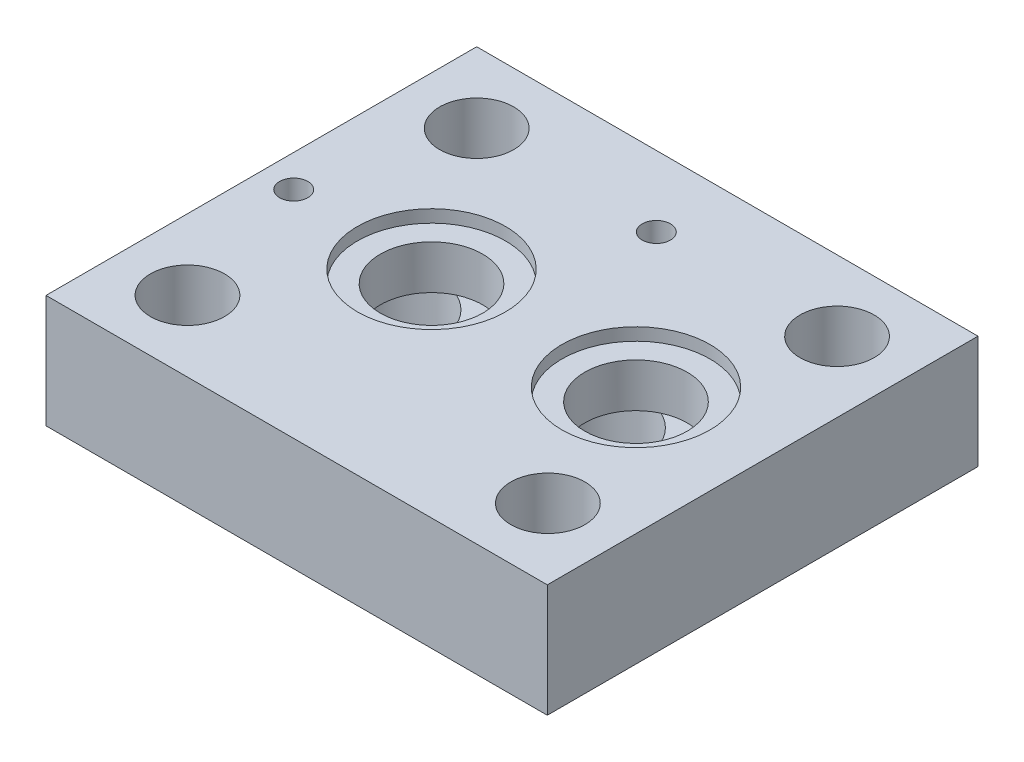
SolidWorks part; units mm, degrees
ref_plane "Front Plane" through (0, 0, 0) normal (0, 0, 1) x (1, 0, 0)
ref_plane "Top Plane" through (0, 0, 0) normal (0, 1, 0) x (1, 0, 0)
ref_plane "Right Plane" through (0, 0, 0) normal (1, 0, 0) x (0, 0, -1)
sketch "Sketch1" plane through (0, 0, 0) normal (0, 1, 0) x (1, 0, 0)
  line L1 (-56.3562, -48.4187) -> (56.3562, -48.4187)
  line L2 (-56.3562, -48.4187) -> (-56.3562, 48.4187)
  line L3 (-56.3562, 48.4187) -> (56.3562, 48.4187)
  line L4 (56.3562, -48.4187) -> (56.3562, 48.4187)
  line L5 (-56.3562, -48.4187) -> (56.3562, 48.4187) construction
  line L6 (-56.3562, 48.4187) -> (56.3562, -48.4187) construction
  point P0 (0, 0)
  dimension "D1" = 56.3562
  dimension "D2" = 48.4187
extrude "Boss-Extrude1" add sketch "Sketch1" along normal mid plane 25.4
sketch "Sketch2" plane through (0, 0, 0) normal (0, 1, 0) x (1, 0, 0)
  circle A0 centre (-40.4812, -32.4803) radius 8.3344
  circle A1 centre (40.5448, -32.4803) radius 8.3344
  circle A2 centre (-40.4812, 32.5437) radius 8.3344
  circle A3 centre (40.5448, 32.5437) radius 8.3344
  point P8 (0, 0)
  dimension "D1" = 16.6687
  dimension "D2" = 16.6687
  dimension "D3" = 16.6687
  dimension "D4" = 16.6687
  dimension "D5" = 81.026
  dimension "D6" = 65.024
  dimension "D7" = 40.4812
  dimension "D8" = 32.4803
extrude "Cut-Extrude2" cut sketch "Sketch2" along normal through all from offset 12.7
sketch "Sketch3" plane through (0, 0, 0) normal (0, 1, 0) x (1, 0, 0)
  circle A0 centre (-27.7812, 0.0317) radius 11.5094
  circle A1 centre (18.1928, 0.0317) radius 11.5094
  point P4 (0, 0)
  dimension "D1" = 23.0187
  dimension "D2" = 23.0187
  dimension "D3" = 45.974
  dimension "D4" = 27.7812
  dimension "D5" = 0.0317
extrude "Cut-Extrude4" cut sketch "Sketch3" along normal blind 12.7 from offset 12.7
sketch "Sketch4" plane through (0, 0, 0) normal (0, 1, 0) x (1, 0, 0)
  circle A0 centre (-18.1293, 0.0317) radius 11.5094
  circle A1 centre (27.8447, 0.0317) radius 11.5094
  point P4 (0, 0)
  dimension "D1" = 23.0187
  dimension "D2" = 23.0187
  dimension "D3" = 45.974
  dimension "D4" = 18.1293
  dimension "D5" = 0.0317
extrude "Cut-Extrude6" cut sketch "Sketch4" against normal blind 12.7 from offset 12.7
sketch "Sketch5" plane through (0, 0, 0) normal (0, 1, 0) x (1, 0, 0)
  circle A0 centre (-18.1293, 0.0317) radius 16.6497
  circle A1 centre (27.8447, 0.0317) radius 16.6497
  point P4 (0, 0)
  dimension "D1" = 33.2994
  dimension "D2" = 33.2994
  dimension "D3" = 45.974
  dimension "D4" = 18.1293
  dimension "D5" = 0.0317
extrude "Cut-Extrude8" cut sketch "Sketch5" against normal blind 2.8194 from offset 12.7
sketch "Sketch6" plane through (0, 0, 0) normal (0, 1, 0) x (1, 0, 0)
  circle A0 centre (49.1808, 0.0317) radius 3.5719
  circle A1 centre (0.1587, -32.4803) radius 3.5719
  point P4 (0, 0)
  dimension "D1" = 7.1437
  dimension "D2" = 7.1438
  dimension "D3" = 49.022
  dimension "D4" = 32.512
  dimension "D5" = 0.1587
  dimension "D6" = 32.4803
extrude "Cut-Extrude10" cut sketch "Sketch6" along normal blind 7.9375 from offset 12.7
sketch "Sketch7" plane through (0, 0, 0) normal (0, 1, 0) x (1, 0, 0)
  circle A0 centre (-49.1172, 0.0317) radius 3.175
  circle A1 centre (-0.0953, 32.5437) radius 3.175
  point P4 (0, 0)
  dimension "D1" = 6.35
  dimension "D2" = 6.35
  dimension "D3" = 49.022
  dimension "D4" = 32.512
  dimension "D5" = 49.1172
  dimension "D6" = 0.0317
extrude "Cut-Extrude12" cut sketch "Sketch7" against normal blind 7.9375 from offset 12.7
